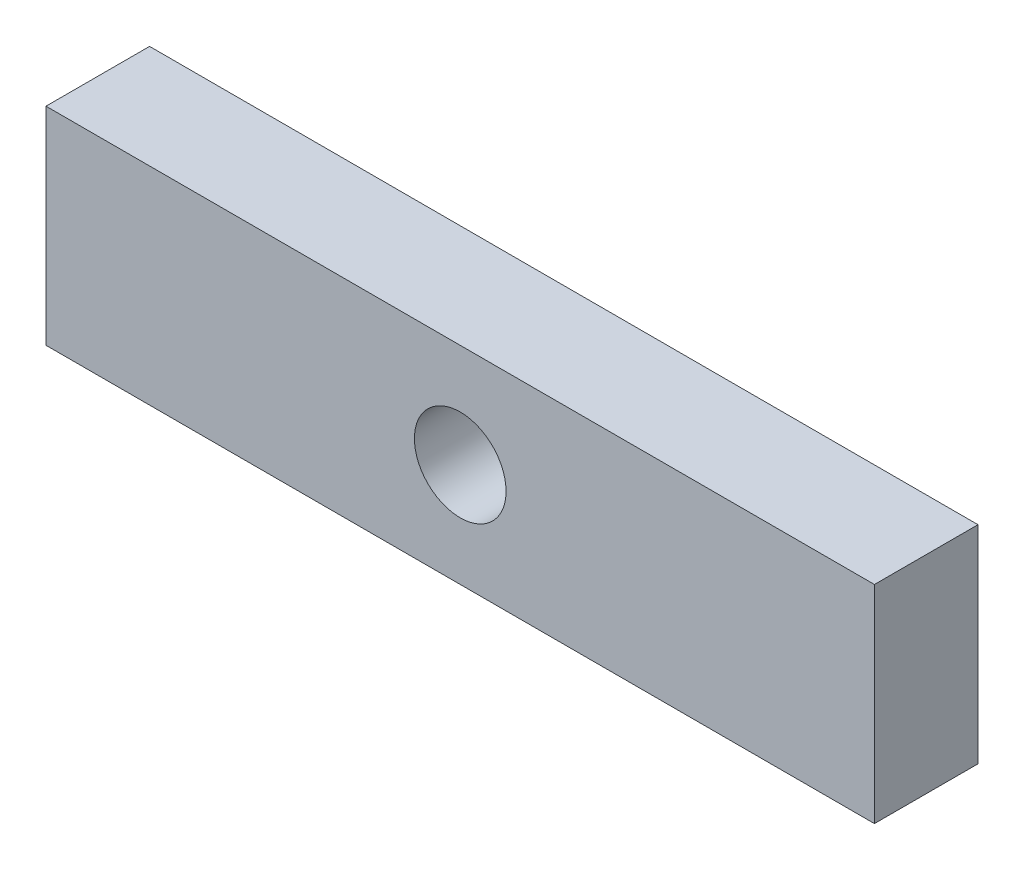
SolidWorks part; units mm, degrees
ref_plane "Front" through (0, 0, 0) normal (0, 0, 1) x (1, 0, 0)
ref_plane "Top" through (0, 0, 0) normal (0, 1, 0) x (1, 0, 0)
ref_plane "Right" through (0, 0, 0) normal (1, 0, 0) x (0, 0, -1)
sketch "Sketch1" plane through (0, 0, 0) normal (0, 0, 1) x (1, 0, 0)
  line L1 (-38.1, -9.525) -> (38.1, -9.525)
  line L2 (-38.1, -9.525) -> (-38.1, 9.525)
  line L3 (-38.1, 9.525) -> (38.1, 9.525)
  line L4 (38.1, -9.525) -> (38.1, 9.525)
  line L5 (-38.1, -9.525) -> (38.1, 9.525) construction
  line L6 (-38.1, 9.525) -> (38.1, -9.525) construction
  point P0 (0, 0)
  dimension "D1" = 19.05
  dimension "D2" = 76.2
extrude "Boss-Extrude1" add sketch "Sketch1" along normal blind 9.525
sketch "Sketch2" plane through (0, 0, 9.525) normal (0, 0, 1) x (1, 0, 0)
  point P0 (0, 0)
hole_wizard "5/16 Clearance Hole1" positions "Sketch4" profile "Sketch3" hole size "5/16" standard "ANSI Inch" end condition through all
sketch "Sketch4" plane through (0, 0, 9.525) normal (0, 0, 1) x (1, 0, 0)
  point P0 (0, 0)
sketch "Sketch3" plane through (0, 0, 9.525) normal (1, 0, 0) x (0, -1, 0)
  line L0 (0, 0) -> (0, 9.525)
  line L1 (0, 9.525) -> (4.2164, 9.525)
  line L2 (4.2164, 9.525) -> (4.2164, 0)
  line L5 (4.2164, 0) -> (0, 0)
  line L11 (0, -6.35) -> (0, 107.95) construction
  dimension "Thru Hole Dia." = 8.4328
  dimension "Thru Hole Depth" = 9.525
